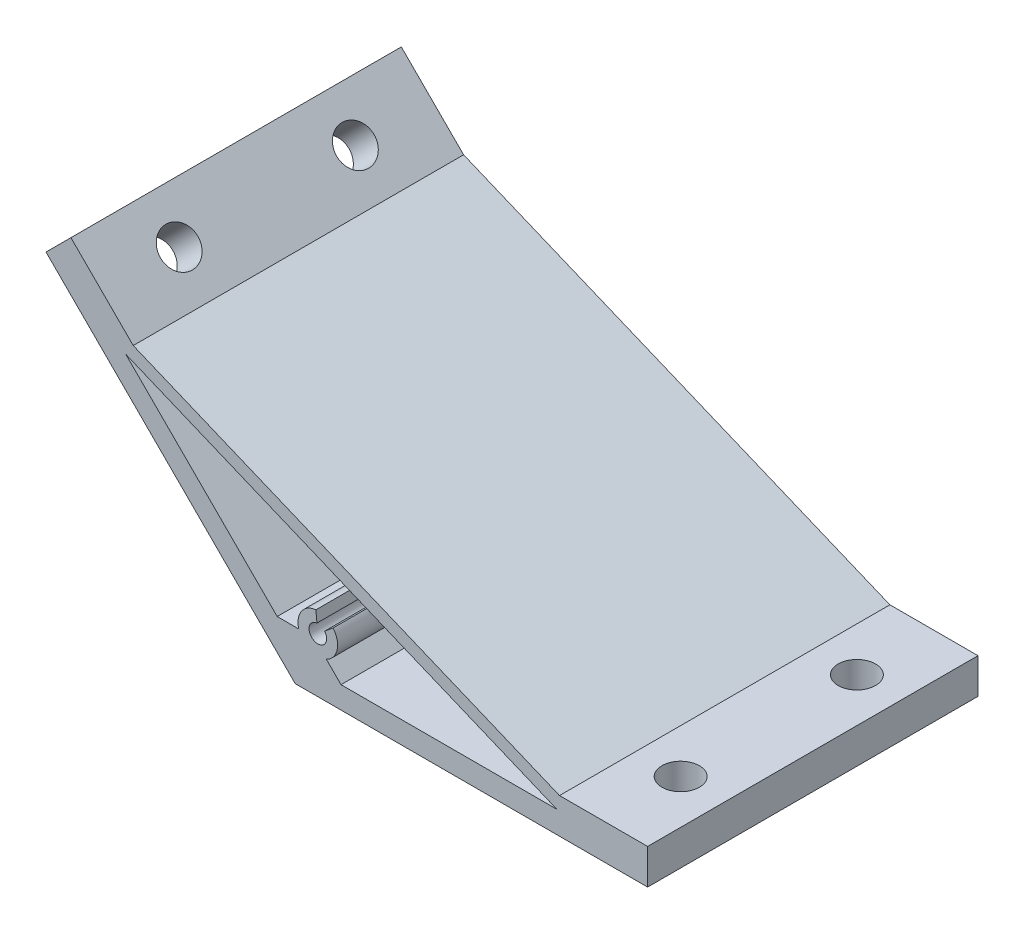
SolidWorks part; units mm, degrees
ref_plane "前视基准面" through (0, 0, 0) normal (0, 0, 1) x (1, 0, 0)
ref_plane "上视基准面" through (0, 0, 0) normal (0, 1, 0) x (1, 0, 0)
ref_plane "右视基准面" through (0, 0, 0) normal (1, 0, 0) x (0, 0, -1)
sketch "草图1" plane through (0, 0, 0) normal (0, 0, 1) x (1, 0, 0)
  line L0 (6992.6877, -1288.6549) -> (7072.6877, -1288.6549)
  line L1 (7003.0909, -1283.6549) -> (7052.0909, -1283.6549)
  line L2 (7052.6877, -1280.6549) -> (7072.6877, -1280.6549)
  line L3 (7003.0909, -1283.6549) -> (7029.4034, -1283.6549)
  line L4 (7072.6877, -1288.6549) -> (7072.6877, -1280.6549)
  line L5 (6997.6265, -1274.2736) -> (6997.3838, -1271.7854)
  line L6 (6999.3656, -1274.9939) -> (7001.2967, -1273.4062)
  line L7 (6992.6877, -1288.6549) -> (6936.1191, -1232.0864)
  line L8 (6988.6024, -1277.4986) -> (6954.2187, -1243.1149)
  line L9 (6955.9181, -1240.5717) -> (6941.776, -1226.4295)
  line L10 (6936.1191, -1232.0864) -> (6941.776, -1226.4295)
  line L11 (6955.9181, -1240.5717) -> (7052.6877, -1280.6549)
  line L12 (6954.2187, -1243.1149) -> (7052.0909, -1283.6549)
  line L13 (7052.0909, -1283.6549) -> (7009.0909, -1283.6549)
  line L14 (7003.0909, -1283.6549) -> (6999.7605, -1280.3246)
  line L15 (6988.6024, -1277.4986) -> (6993.4934, -1277.4986)
  arc A0 (6997.3838, -1271.7854) -> (6993.4934, -1277.4986) centre (6997.8207, -1276.2641) ccw
  arc A1 (6999.7605, -1280.3246) -> (7001.2967, -1273.4062) centre (6997.8207, -1276.2641) ccw
  arc A2 (6997.6265, -1274.2736) -> (6999.3656, -1274.9939) centre (6997.8207, -1276.2641) ccw
extrude "凸台-拉伸1" add sketch "草图1" along normal mid plane 75 contours L11 L9 L10 L7 L0 L4 L2 A2 L5 A0 L15 L8 L12 L1 L3 L14 A1 L6
hole_wizard "Ø8.5 (8.5) 直径孔1" positions "草图3" profile "草图2" hole size "Ø8.5" standard "GB" end condition through all
sketch "草图3" plane through (2852.0164, 2852.0164, 0) normal (-0.7071, -0.7071, 0) x (0.7071, -0.7071, 0)
  line L1 (5775.7935, 37.5) -> (5775.7935, -37.5) construction
  line L2 (5795.7935, -37.5) -> (5775.7935, -37.5) construction
  point P1 (5785.7935, -20)
  point P18 (5785.7935, 20)
  dimension "D1" = 10
  dimension "D2" = 17.5
  dimension "D3" = 2
sketch "草图2" plane through (6943.1902, -1239.1575, -20) normal (0, 0, 1) x (0.7071, -0.7071, 0)
  line L0 (0, 0) -> (0, 100.5685)
  line L1 (0, 100.5685) -> (4.25, 100.5685)
  line L2 (4.25, 100.5685) -> (4.25, 0)
  line L5 (4.25, 0) -> (0, 0)
  line L11 (0, -6.35) -> (0, 107.95) construction
  dimension "通孔孔直径" = 8.5
  dimension "通孔孔深度" = 100.5685
hole_wizard "Ø8.5 (8.5) 直径孔2" positions "草图5" profile "草图4" hole size "Ø8.5" standard "GB" end condition through all
sketch "草图5" plane through (0, -1288.6549, 0) normal (0, -1, 0) x (1, 0, 0)
  line L1 (7072.6877, 37.5) -> (7072.6877, -37.5) construction
  line L2 (7052.6877, -37.5) -> (7072.6877, -37.5) construction
  point P0 (7062.6877, -20)
  point P17 (7062.6877, 20)
  dimension "D1" = 17.5
  dimension "D2" = 10
  dimension "D3" = 2
sketch "草图4" plane through (7062.6877, -1288.6549, -20) normal (1, 0, 0) x (0, 0, -1)
  line L0 (0, 0) -> (0, 62.2254)
  line L1 (0, 62.2254) -> (4.25, 62.2254)
  line L2 (4.25, 62.2254) -> (4.25, 0)
  line L5 (4.25, 0) -> (0, 0)
  line L11 (0, -6.35) -> (0, 107.95) construction
  dimension "通孔孔直径" = 8.5
  dimension "通孔孔深度" = 62.2254
